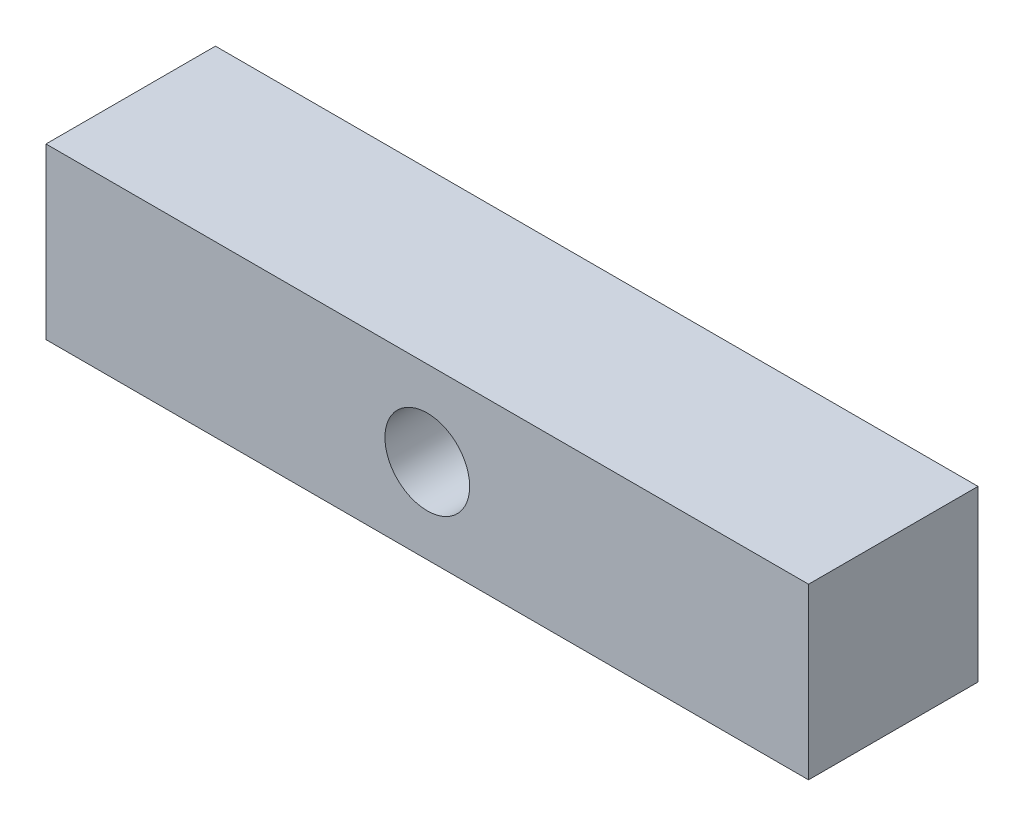
SolidWorks part; units mm, degrees
ref_plane "Front Plane" through (0, 0, 0) normal (0, 0, 1) x (1, 0, 0)
ref_plane "Top Plane" through (0, 0, 0) normal (0, 1, 0) x (1, 0, 0)
ref_plane "Right Plane" through (0, 0, 0) normal (1, 0, 0) x (0, 0, -1)
sketch "Sketch1" plane through (0, 0, 0) normal (0, 0, 1) x (1, 0, 0)
  line L1 (0, 0) -> (114.3, 0)
  line L2 (0, 0) -> (0, 25.4)
  line L3 (0, 25.4) -> (114.3, 25.4)
  line L4 (114.3, 0) -> (114.3, 25.4)
  dimension "D1" = 114.3
  dimension "D2" = 25.4
extrude "Boss-Extrude1" add sketch "Sketch1" along normal blind 25.4
sketch "Sketch2" plane through (0, 0, 25.4) normal (0, 0, 1) x (1, 0, 0)
  line L0 (114.3, 25.4) -> (0, 25.4) construction
  line L1 (114.3, 0) -> (114.3, 25.4) construction
  circle A0 centre (57.15, 12.7) radius 6.35
  dimension "D1" = 12.7
  dimension "D3" = 12.7
  dimension "D2" = 57.15
extrude "Cut-Extrude1" cut sketch "Sketch2" against normal through all
